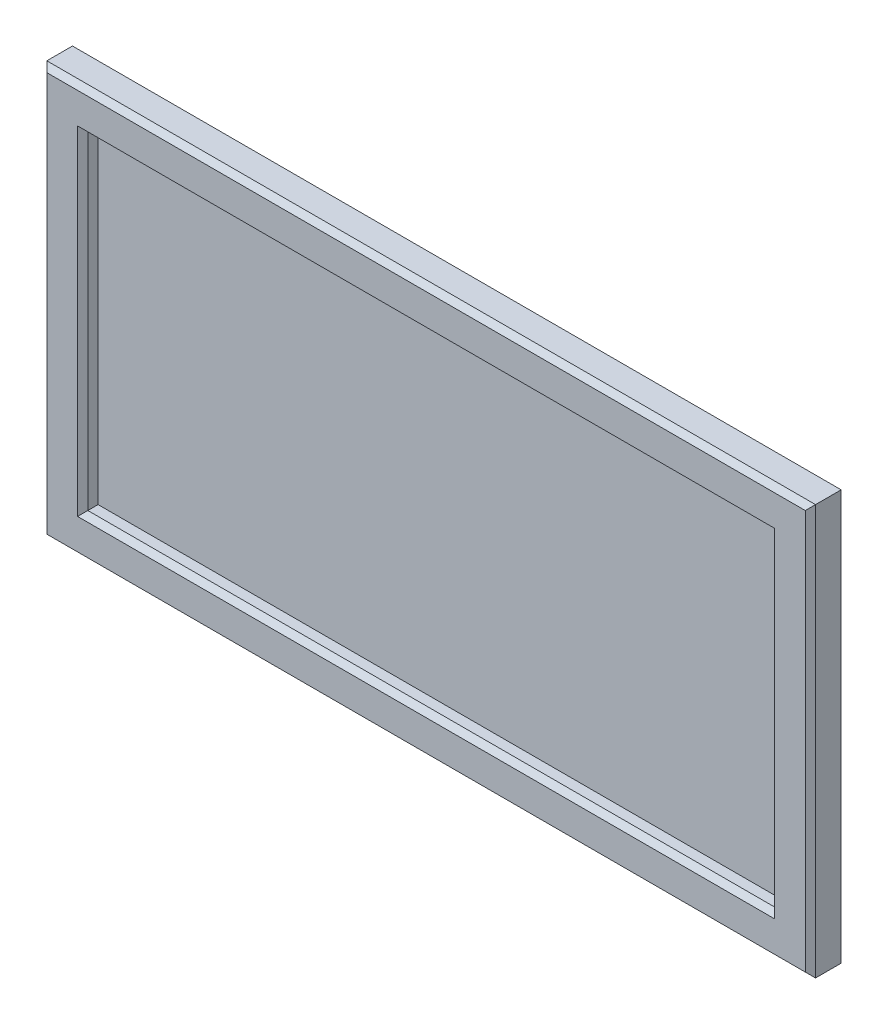
SolidWorks part; units mm, degrees
ref_plane "Спереди" through (0, 0, 0) normal (0, 0, 1) x (1, 0, 0)
ref_plane "Сверху" through (0, 0, 0) normal (0, 1, 0) x (1, 0, 0)
ref_plane "Справа" through (0, 0, 0) normal (1, 0, 0) x (0, 0, -1)
other "Configuration Table"
sketch "Эскиз1" plane through (0, 0, 0) normal (0, 0, 1) x (1, 0, 0)
  line L0 (80, 80) -> (80, 720)
  line L1 (0, 0) -> (1500, 0)
  line L2 (0, 0) -> (0, 800)
  line L3 (0, 800) -> (1500, 800)
  line L4 (1500, 0) -> (1500, 800)
  line L5 (80, 720) -> (1420, 720)
  line L6 (1420, 80) -> (1420, 720)
  line L7 (80, 80) -> (1420, 80)
  dimension "D1" = 1500
  dimension "D3" = 800
  dimension "D2" = 80
extrude "Бобышка-Вытянуть1" add sketch "Эскиз1" along normal blind 60
chamfer "Фаска1" distance 10 angle 45 8 edges at (1420, 400, 60) (750, 720, 60) (80, 400, 60) (750, 80, 60) (750, 800, 60) (1500, 400, 60) (750, 0, 60) (0, 400, 60)
sketch "Эскиз2" plane through (0, 0, 0) normal (0, 0, -1) x (-1, 0, 0)
  line L1 (-1457.1483, 737.8745) -> (-41.8597, 737.8745)
  line L2 (-1457.1483, 737.8745) -> (-1457.1483, 37.5134)
  line L3 (-1457.1483, 37.5134) -> (-41.8597, 37.5134)
  line L4 (-41.8597, 737.8745) -> (-41.8597, 37.5134)
  point P4 (-1457.1483, 737.8745)
extrude "Бобышка-Вытянуть2" add sketch "Эскиз2" against normal blind 10 from offset 20 separate body
